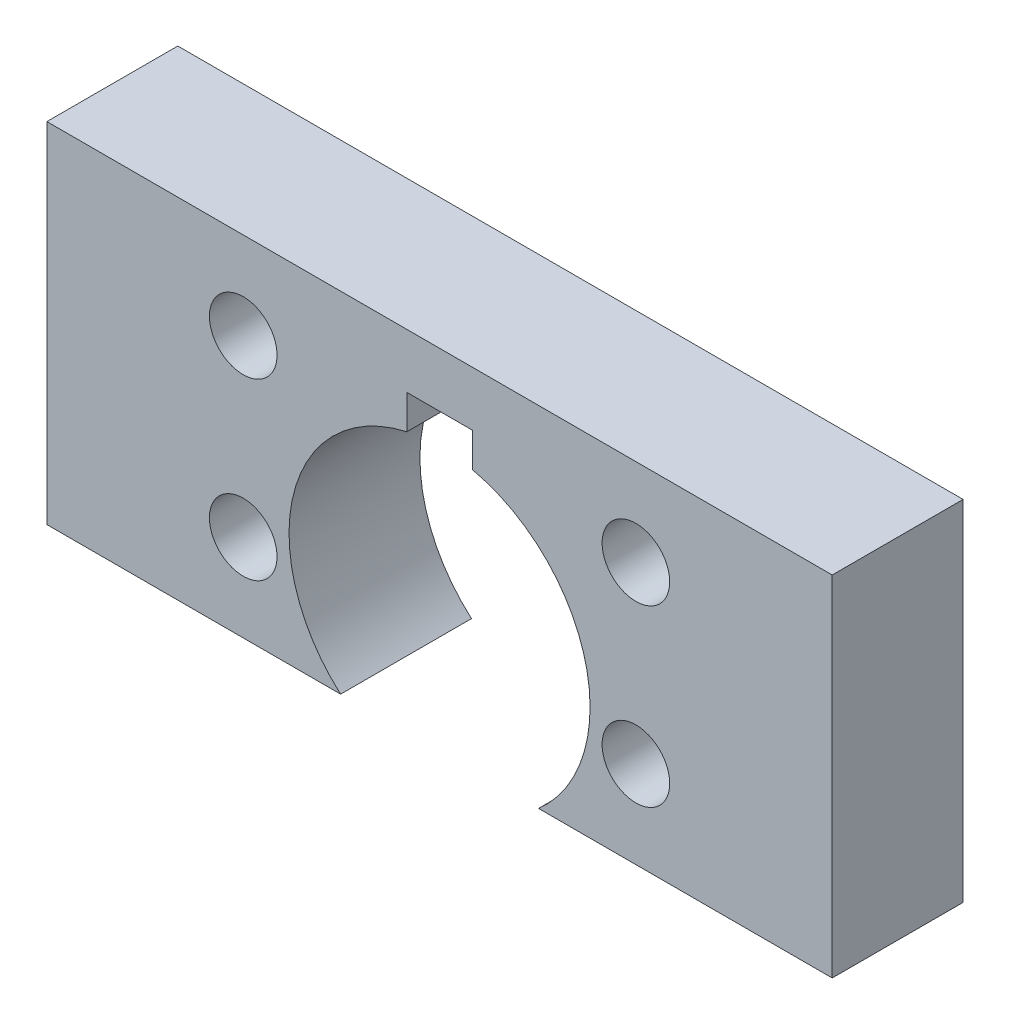
SolidWorks part; units mm, degrees
ref_plane "Płaszczyzna przednia" through (0, 0, 0) normal (0, 0, 1) x (1, 0, 0)
ref_plane "Płaszczyzna górna" through (0, 0, 0) normal (0, 1, 0) x (1, 0, 0)
ref_plane "Płaszczyzna prawa" through (0, 0, 0) normal (1, 0, 0) x (0, 0, -1)
sketch "Szkic1" plane through (0, 0, 0) normal (0, 0, 1) x (1, 0, 0)
  line L0 (71.503, 0) -> (35.503, 0)
  line L1 (71.503, 0) -> (71.503, -16)
  line L2 (35.503, 0) -> (35.503, -16)
  line L3 (71.503, -16) -> (35.503, -16)
  dimension "D1" = 36
  dimension "D2" = 16
extrude "Dodanie-wyciągnięcie1" add sketch "Szkic1" against normal blind 6
sketch "Szkic2" plane through (0, 0, 0) normal (0, 0, 1) x (1, 0, 0)
  line L0 (35.503, -16) -> (71.503, -16) construction
  line L1 (35.503, 0) -> (35.503, -16) construction
  line L2 (55.003, -4.065) -> (55.003, -2.5)
  line L3 (57.393, -16) -> (49.613, -16)
  line L4 (55.003, -2.5) -> (52.003, -2.5)
  line L5 (52.003, -4.065) -> (52.003, -2.5)
  line L6 (57.393, -16) -> (57.393, -16.4989)
  line L7 (49.613, -16) -> (49.613, -16.4989)
  line L8 (35.503, -16) -> (71.503, -16) construction
  arc A0 (52.003, -4.065) -> (49.613, -16.4989) centre (53.503, -10.8) ccw
  arc A1 (57.393, -16.4989) -> (55.003, -4.065) centre (53.503, -10.8) ccw
  dimension "D1" = 5.2
  dimension "D2" = 13.8
  dimension "D3" = 18
  dimension "D4" = 8.3
  dimension "D5" = 1.5
  dimension "D6" = 1.5
  dimension "D7" = 3.89
  dimension "D8" = 3.89
  dimension "D9" = 0
extrude "Wytnij-wyciągnięcie1" cut sketch "Szkic2" against normal blind 6
sketch "Szkic3" plane through (0, 0, -6) normal (0, 0, -1) x (-1, 0, 0)
  circle A0 centre (-44.503, -12) radius 1.55 construction
  circle A1 centre (-44.503, -12) radius 1.55
  circle A6 centre (-44.503, -4) radius 1.55 construction
  circle A7 centre (-62.503, -4) radius 1.55 construction
  circle A8 centre (-62.503, -12) radius 1.55 construction
  circle A9 centre (-44.503, -4) radius 1.55
  circle A10 centre (-62.503, -4) radius 1.55
  circle A11 centre (-62.503, -12) radius 1.55
extrude "Wytnij-wyciągnięcie2" cut sketch "Szkic3" against normal through all
